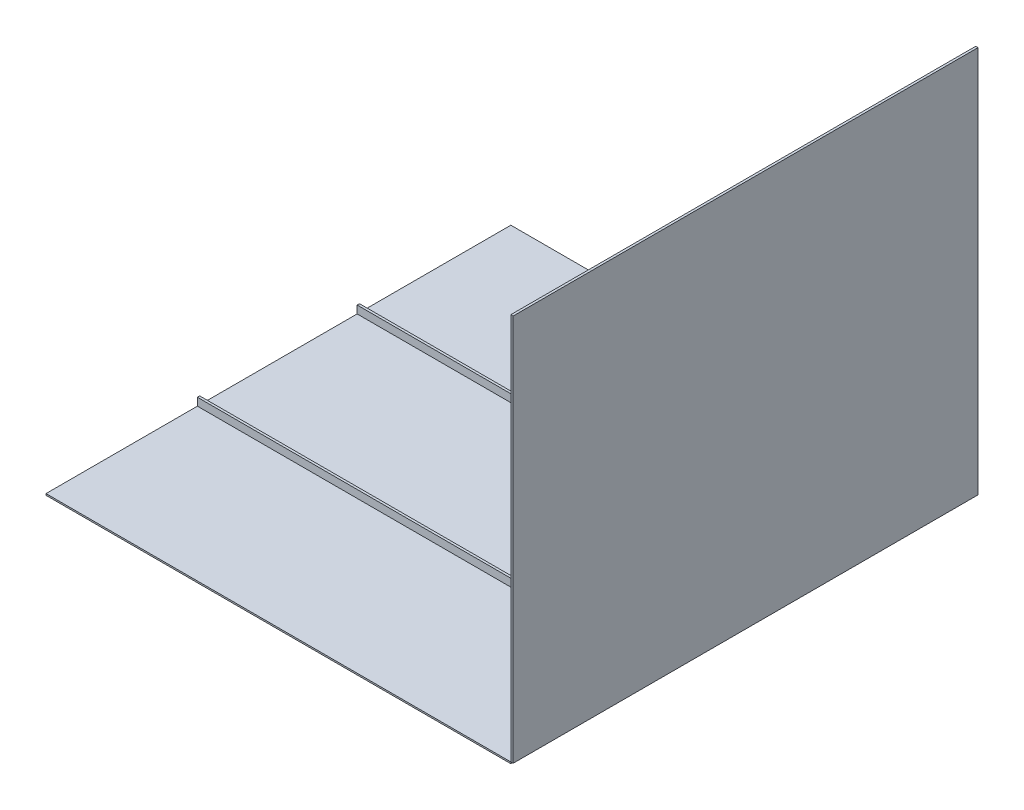
SolidWorks part; units mm, degrees
ref_plane "前视基准面" through (0, 0, 0) normal (0, 0, 1) x (1, 0, 0)
ref_plane "上视基准面" through (0, 0, 0) normal (0, 1, 0) x (1, 0, 0)
ref_plane "右视基准面" through (0, 0, 0) normal (1, 0, 0) x (0, 0, -1)
other "Configuration Table"
sketch "草图1" plane through (0, 0, 0) normal (0, 1, 0) x (1, 0, 0)
  line L1 (300, -300) -> (-300, -300)
  line L2 (300, -300) -> (300, 300)
  line L3 (300, 300) -> (-300, 300)
  line L4 (-300, -300) -> (-300, 300)
  line L5 (300, -300) -> (-300, 300) construction
  line L6 (300, 300) -> (-300, -300) construction
  point P0 (0, 0)
  dimension "D1" = 600
  dimension "D2" = 600
extrude "凸台-拉伸1" add sketch "草图1" along normal blind 2
sketch "草图2" plane through (0, 2, 0) normal (0, 1, 0) x (1, 0, 0)
  line L1 (300, 300) -> (303, 300)
  line L2 (300, 300) -> (300, -300)
  line L3 (300, -300) -> (303, -300)
  line L4 (303, 300) -> (303, -300)
  dimension "D1" = 3
  dimension "D2" = 600
extrude "凸台-拉伸2" add sketch "草图2" along normal blind 500 separate body
sketch "草图4" plane through (0, 2, 0) normal (0, 1, 0) x (1, 0, 0)
  line L0 (-300, 300) -> (-300, -300) construction
  line L1 (-300, 104.6) -> (292.256, 104.6)
  line L2 (-300, 104.6) -> (-300, 101.6)
  line L3 (-300, 101.6) -> (292.256, 101.6)
  line L4 (292.256, 104.6) -> (292.256, 101.6)
  line L6 (-300, 0) -> (296.6941, 0) construction
  line L7 (-300, -101.6) -> (299.2871, -101.6)
  line L8 (-300, -101.6) -> (-300, -104.6)
  line L9 (-300, -104.6) -> (299.2871, -104.6)
  line L10 (299.2871, -101.6) -> (299.2871, -104.6)
  dimension "D1" = 3
  dimension "D2" = 3
  dimension "D3" = 101.6
  dimension "D4" = 101.6
extrude "凸台-拉伸6" add sketch "草图4" along normal blind 10
